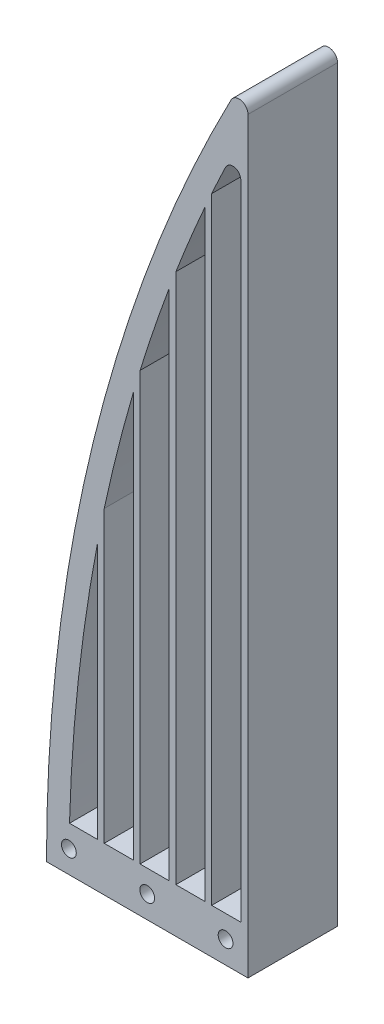
SolidWorks part; units mm, degrees
material "Silicon"
ref_plane "Front Plane" through (0, 0, 0) normal (0, 0, 1) x (1, 0, 0)
ref_plane "Top Plane" through (0, 0, 0) normal (0, 1, 0) x (1, 0, 0)
ref_plane "Right Plane" through (0, 0, 0) normal (1, 0, 0) x (0, 0, -1)
sketch "Sketch1" plane through (0, 0, 0) normal (0, 1, 0) x (1, 0, 0)
  line L1 (-9.5, 8) -> (9.5, 8) construction
  line L2 (-9.5, 8) -> (-9.5, -8) construction
  line L3 (-9.5, -8) -> (9.5, -8) construction
  line L4 (9.5, 8) -> (9.5, -8) construction
  line L5 (-9.5, 8) -> (9.5, -8) construction
  line L6 (-9.5, -8) -> (9.5, 8) construction
  line L7 (12, 10.5) -> (-12, 10.5)
  line L8 (12, 10.5) -> (12, -10.5)
  line L9 (12, -10.5) -> (-12, -10.5)
  line L10 (-12, 10.5) -> (-12, -10.5)
  line L11 (12, 10.5) -> (-12, -10.5) construction
  line L12 (12, -10.5) -> (-12, 10.5) construction
  circle A0 centre (-9.5, 8) radius 1.625
  circle A1 centre (9.5, 8) radius 1.625
  circle A2 centre (9.5, -8) radius 1.625
  circle A3 centre (-9.5, -8) radius 1.625
  point P0 (0, 0)
  point P10 (0, 0)
  dimension "D3" = 3.25
  dimension "D1" = 24
  dimension "D2" = 21
  dimension "D4" = 19
  dimension "D5" = 16
extrude "Boss-Extrude1" [suppressed] add sketch "Sketch1" along normal blind 7.5
sketch "Sketch5" plane through (0, 0, 0) normal (0, 0, 1) x (1, 0, 0)
  line L0 (0, 0) -> (0, 167.0412)
  line L1 (-45, 0) -> (0, 0)
  line L2 (-1.6, 10) -> (-39.8602, 10)
  line L98 (-1.6, 10) -> (-1.6, 153.5644)
  line L99 (-45, 0) -> (-45, 5) construction
  line L102 (-39.9651, 5) -> (-5, 5) construction
  line L103 (-5, 5) -> (-5, 154.3355) construction
  line L104 (0, 0) -> (0, 175) construction
  arc A1 (-3.7727, 167.9673) -> (-45, 0) centre (317.7778, 0) ccw
  arc A24 (-5, 154.3355) -> (-39.8602, 10) centre (317.7778, 0) ccw
  arc A25 (-5, 154.3355) -> (-39.9651, 5) centre (317.7778, 0) ccw construction
  arc A26 (-1.6, 153.5644) -> (-5, 154.3355) centre (-3.3874, 153.5644) ccw
  arc A27 (0, 175) -> (-45, 0) centre (317.7778, 0) ccw construction
  arc A28 (0, 167.0412) -> (-3.7727, 167.9673) centre (-2, 167.0412) ccw
  point P16 (0, 175)
  dimension "D7" = 2
  dimension "D2" = 175
  dimension "D5" = 10
  dimension "D6" = 1.6
  dimension "D1" = 5
  dimension "D3" = 45
  dimension "D4" = 5
extrude "Boss-Extrude4" add sketch "Sketch5" along normal blind 20
sketch "Sketch10" plane through (0, 0, 20) normal (0, 0, 1) x (1, 0, 0)
  line L0 (-39.6854, 15) -> (-1.6, 15)
  line L1 (-1.6, 10) -> (-1.6, 153.5644) construction
  line L2 (-1.6, 16.6) -> (-39.6147, 16.6)
  line L3 (-39.8602, 10) -> (-1.6, 10) construction
  line L4 (0, 10) -> (75, 10) construction
  line L5 (0, 0) -> (0, 167.0412) construction
  line L6 (-38.5345, 26.9605) -> (-0.6577, 22.9795)
  line L7 (-0.4905, 24.5707) -> (-38.2969, 28.5443)
  line L8 (-36.1397, 38.7352) -> (1.1135, 30.8168)
  line L9 (1.4461, 32.3818) -> (-35.7379, 40.2855)
  line L10 (-32.5272, 50.195) -> (3.6942, 38.426)
  line L11 (4.1886, 39.9477) -> (-31.9655, 51.6949)
  line L12 (-27.7367, 61.2145) -> (7.0561, 45.7238)
  line L13 (7.7069, 47.1854) -> (-27.0213, 62.6474)
  line L14 (-21.8205, 71.6728) -> (11.1625, 52.6301)
  line L15 (11.9625, 54.0158) -> (-20.9592, 73.0231)
  line L20 (0, 68.0707) -> (75, 10) construction
  line L21 (-1.6, 69.3095) -> (-28.4662, 90.1114)
  line L22 (-1.6, 70.9537) -> (-28.1077, 91.4779)
  line L23 (3.8607, 75.76) -> (-21.0903, 98.8242)
  line L24 (4.0039, 77.3979) -> (-20.614, 100.1543)
  line L25 (9.8627, 81.7099) -> (-12.9831, 106.861)
  line L26 (10.1482, 83.3291) -> (-12.3927, 108.1445)
  line L27 (16.3605, 87.1142) -> (-4.2063, 114.1607)
  line L28 (16.7861, 88.7023) -> (-3.5063, 115.3878)
  line L29 (23.3046, 91.9315) -> (5.1733, 120.6676)
  line L30 (23.8669, 93.4765) -> (5.9776, 121.8291)
  arc A0 (-5, 154.3355) -> (-39.8602, 10) centre (317.7778, 0) ccw construction
  arc A1 (-5, 154.3355) -> (-39.8602, 10) centre (317.7778, 0) ccw
  point P54 (75, 10)
  point P67 (75, 10)
  dimension "D1" = 1.6
  dimension "D2" = 5
  dimension "D5" = 6
  dimension "D6" = 1.3
  dimension "D9" = 5
  dimension "D7" = 7.75
  dimension "D3" = 144.3355
  dimension "D4" = 6
  dimension "D8" = 5
sketch "Sketch11" plane through (0, 0, 20) normal (0, 0, 1) x (1, 0, 0)
  line L0 (-39.6854, 15) -> (-1.6, 15)
  line L1 (-1.6, 10) -> (-1.6, 153.5644) construction
  line L2 (-1.6, 15) -> (-1.6, 16.6)
  line L3 (-39.6147, 16.6) -> (-1.6, 16.6)
  line L4 (-38.9792, 27.0072) -> (-1.6, 23.0785)
  line L5 (-38.5345, 26.9605) -> (-0.6577, 22.9795) construction
  line L6 (-38.8548, 28.603) -> (-1.6, 24.6873)
  line L7 (-0.4905, 24.5707) -> (-38.2969, 28.5443) construction
  line L8 (-37.857, 39.1002) -> (-1.6, 31.3935)
  line L9 (-37.6777, 40.6978) -> (-1.6, 33.0293)
  line L10 (1.4461, 32.3818) -> (-35.7379, 40.2855) construction
  line L11 (-36.1397, 38.7352) -> (1.1135, 30.8168) construction
  line L12 (-36.2862, 51.4164) -> (-1.6, 40.1462)
  line L13 (-32.5272, 50.195) -> (3.6942, 38.426) construction
  line L14 (-36.0493, 53.0218) -> (-1.6, 41.8285)
  line L15 (4.1886, 39.9477) -> (-31.9655, 51.6949) construction
  line L16 (-34.2115, 64.0973) -> (-1.6, 49.5777)
  line L17 (-27.7367, 61.2145) -> (7.0561, 45.7238) construction
  line L18 (-33.913, 65.7158) -> (-1.6, 51.3291)
  line L19 (7.7069, 47.1854) -> (-27.0213, 62.6474) construction
  line L29 (-28.4662, 90.1114) -> (-1.6, 69.3095)
  line L31 (-28.1077, 91.4779) -> (-1.6, 70.9537)
  line L33 (-1.6, 61.8461) -> (-31.1856, 78.9273)
  line L35 (-31.5516, 77.2911) -> (-1.6, 59.9985)
  line L36 (-25.0168, 102.4538) -> (-1.6, 80.8077)
  line L37 (3.8607, 75.76) -> (-21.0903, 98.8242) construction
  line L38 (-24.5999, 103.8387) -> (-1.6, 82.578)
  line L39 (4.0039, 77.3979) -> (-20.614, 100.1543) construction
  line L40 (-20.8402, 115.511) -> (-1.6, 94.3293)
  line L41 (9.8627, 81.7099) -> (-12.9831, 106.861) construction
  line L42 (-20.3584, 116.914) -> (-1.6, 96.2628)
  line L43 (10.1482, 83.3291) -> (-12.3927, 108.1445) construction
  line L44 (-15.7847, 129.387) -> (-1.6, 110.7332)
  line L45 (16.3605, 87.1142) -> (-4.2063, 114.1607) construction
  line L46 (-15.2308, 130.8061) -> (-1.6, 112.8809)
  line L47 (16.7861, 88.7023) -> (-3.5063, 115.3878) construction
  line L48 (-1.6, 23.0785) -> (-1.6, 24.6873)
  line L49 (-1.6, 31.3935) -> (-1.6, 33.0293)
  line L50 (-1.6, 40.1462) -> (-1.6, 41.8285)
  line L51 (-1.6, 49.5777) -> (-1.6, 51.3291)
  line L53 (-1.6, 110.7332) -> (-1.6, 112.8809)
  line L54 (-1.6, 94.3293) -> (-1.6, 96.2628)
  line L55 (-1.6, 80.8077) -> (-1.6, 82.578)
  line L59 (-21.8205, 71.6728) -> (11.1625, 52.6301) construction
  line L60 (11.9625, 54.0158) -> (-20.9592, 73.0231) construction
  line L61 (-1.6, 59.9985) -> (-1.6, 61.8461)
  line L62 (-9.6623, 144.1803) -> (-1.6, 131.4025)
  line L63 (-9.0282, 145.6117) -> (-1.6, 133.8387)
  line L64 (23.8669, 93.4765) -> (5.9776, 121.8291) construction
  line L65 (23.3046, 91.9315) -> (5.1733, 120.6676) construction
  line L66 (-1.6, 133.8387) -> (-1.6, 131.4025)
  arc A0 (-5, 154.3355) -> (-39.8602, 10) centre (317.7778, 0) ccw construction
  arc A2 (-39.6147, 16.6) -> (-39.6854, 15) centre (317.7778, 0) ccw
  arc A8 (-24.5999, 103.8387) -> (-25.0168, 102.4538) centre (317.7778, 0) ccw
  arc A13 (-9.0282, 145.6117) -> (-9.6623, 144.1803) centre (317.7778, 0) ccw
  arc A14 (-39.6147, 16.6) -> (-39.6854, 15) centre (317.7778, 0) ccw
  arc A15 (-38.8548, 28.603) -> (-38.9792, 27.0072) centre (317.7778, 0) ccw
  arc A16 (-37.6777, 40.6978) -> (-37.857, 39.1002) centre (317.7778, 0) ccw
  arc A17 (-36.0493, 53.0218) -> (-36.2862, 51.4164) centre (317.7778, 0) ccw
  arc A18 (-33.913, 65.7158) -> (-34.2115, 64.0973) centre (317.7778, 0) ccw
  arc A19 (-31.1856, 78.9273) -> (-31.5516, 77.2911) centre (317.7778, 0) ccw
  arc A20 (-28.1077, 91.4779) -> (-28.4662, 90.1114) centre (317.7778, 0) ccw
  arc A21 (-24.5999, 103.8387) -> (-25.0168, 102.4538) centre (317.7778, 0) ccw
  arc A22 (-20.3584, 116.914) -> (-20.8402, 115.511) centre (317.7778, 0) ccw
  arc A23 (-15.2308, 130.8061) -> (-15.7847, 129.387) centre (317.7778, 0) ccw
sketch "Sketch12" plane through (0, 0, 20) normal (0, 0, 1) x (1, 0, 0)
  line L0 (-40, 5) -> (-22.5, 5) construction
  line L1 (-39.8602, 10) -> (-1.6, 10) construction
  line L2 (-22.5, 0) -> (-22.5, 10) construction
  line L3 (-45, 0) -> (0, 0) construction
  line L4 (-22.5, 5) -> (-5, 5) construction
  line L6 (-5, 5) -> (0, 5) construction
  line L7 (0, 0) -> (0, 167.0412) construction
  circle A1 centre (-40, 5) radius 1.65
  circle A2 centre (-22.5, 5) radius 1.65
  circle A3 centre (-5, 5) radius 1.65
  dimension "D1" = 3.3
  dimension "D2" = 17.5
extrude "Cut-Extrude1" cut sketch "Sketch12" against normal through all
sketch "Sketch14" plane through (0, 0, 20) normal (0, 0, 1) x (1, 0, 0)
  line L0 (-1.6, 10) -> (-1.6, 153.5644) construction
  line L2 (-1.6, 158.5644) -> (-1.6, 10)
  line L3 (-1.6, 158.5644) -> (-0.1, 158.5644)
  line L4 (-1.6, 10) -> (-0.1, 10)
  line L5 (-0.1, 158.5644) -> (-0.1, 10)
  dimension "D1" = 0
  dimension "D2" = 5
  dimension "D3" = 1.5
extrude "Boss-Extrude5" add sketch "Sketch14" against normal blind 20
sketch "Sketch17" plane through (0, 0, 20) normal (0, 0, 1) x (1, 0, 0)
  line L0 (-45, 0) -> (0, 0)
  line L1 (0, 0) -> (0, 167.0412)
  line L2 (-120.6382, 868.826) -> (-109.1292, -31.174)
  line L3 (-109.1292, -31.174) -> (790.8708, -19.665)
  line L4 (790.8708, -19.665) -> (784.1337, 507.1754)
  line L5 (784.1337, 507.1754) -> (-120.6382, 868.826)
  arc A1 (0, 167.0412) -> (-3.7727, 167.9673) centre (-2, 167.0412) ccw
  arc A3 (-3.7727, 167.9673) -> (-45, 0) centre (317.7778, 0) ccw
  dimension "D1" = 900
  dimension "D2" = 900
extrude "Cut-Extrude2" cut sketch "Sketch17" against normal blind 20
sketch "Sketch18" plane through (0, 0, 20) normal (0, 0, 1) x (1, 0, 0)
  line L0 (-45, 0) -> (0, 0)
  line L1 (0, 0) -> (0, 167.0412)
  line L2 (10.5677, -7.1526) -> (26.572, 318.7821)
  line L3 (26.572, 318.7821) -> (-234.7297, 306.4711)
  line L4 (-234.7297, 306.4711) -> (-205.7988, -46.8557)
  line L5 (-205.7988, -46.8557) -> (10.5677, -7.1526)
  arc A0 (0, 167.0412) -> (-3.7727, 167.9673) centre (-2, 167.0412) ccw
  arc A1 (-3.7727, 167.9673) -> (-45, 0) centre (317.7778, 0) ccw
extrude "Cut-Extrude3" cut sketch "Sketch18" against normal blind 30
pattern_linear "LPattern2" count 5 spacing 8 count 5 spacing 8 along (-1, 0, 0) of "Boss-Extrude5"
sketch "Sketch19" plane through (0, 0, 20) normal (0, 0, 1) x (1, 0, 0)
  line L0 (-45, 0) -> (0, 0)
  line L1 (0, 0) -> (0, 167.0412)
  line L2 (-113.91, -19.1316) -> (183.2467, -29.1763)
  line L3 (183.2467, -29.1763) -> (134.6972, 220.2679)
  line L4 (134.6972, 220.2679) -> (-171.2487, 235.335)
  line L5 (-171.2487, 235.335) -> (-113.91, -19.1316)
  arc A0 (0, 167.0412) -> (-3.7727, 167.9673) centre (-2, 167.0412) ccw
  arc A1 (-3.7727, 167.9673) -> (-45, 0) centre (317.7778, 0) ccw
extrude "Cut-Extrude4" cut sketch "Sketch19" against normal blind 30
equation "\"Middle Finger Width\"= 30mm"
equation "\"Finger Length\"= 45"
equation "\"Finger Height\"= \"Finger Length\" * 3.5"
equation "\"D3@Sketch5\"=\"Finger Length\""
equation "\"Base Height\"= 10mm"
equation "\"D1@Sketch5\"= \"Base Height\" / 2"
equation "\"D5@Sketch5\"= \"Base Height\""
equation "\"Thick Walls\"= 1.6mm"
equation "\"Thin Walls\"= 1.3mm"
equation "\"D6@Sketch5\"=\"Thick Walls\""
equation "\"D2@Sketch10\"=\"Base Height\"/2"
equation "\"D1@Sketch10\"=\"Thick Walls\" "
equation "\"D6@Sketch10\"=\"Thin Walls\""
equation "\"D1@Boss-Extrude4\"  = 2 * \"Middle Finger Width\" /3"
equation "\"Outer Finger Width\"= 2 * \"Middle Finger Width\" / 3"
